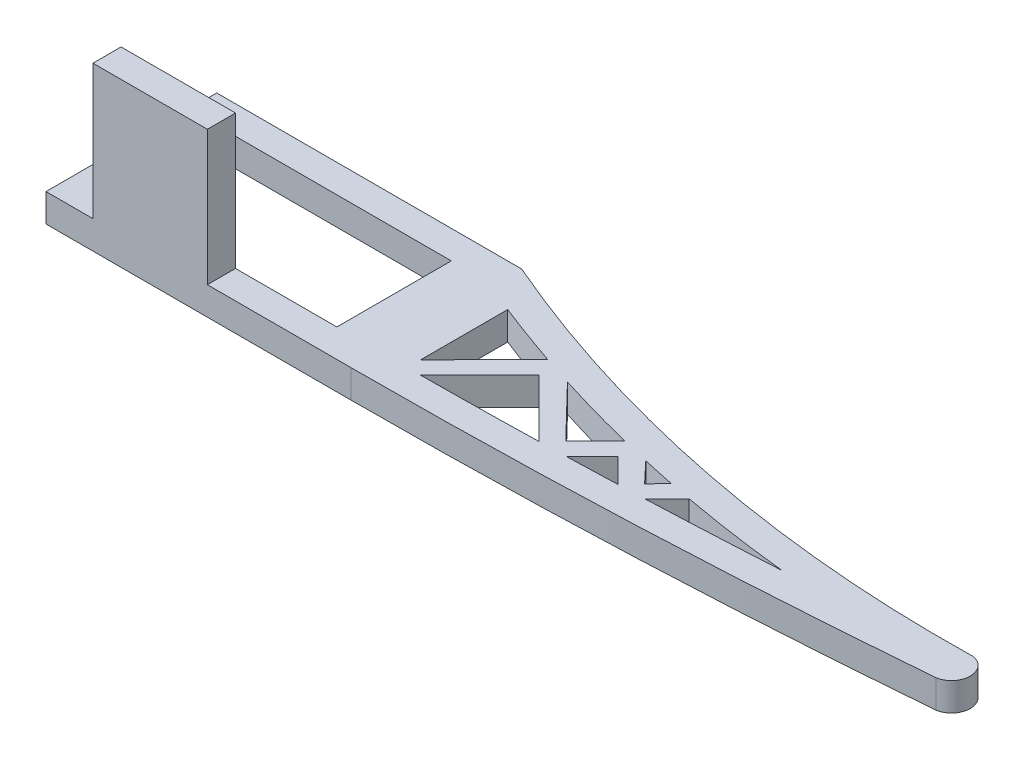
SolidWorks part; units mm, degrees
ref_plane "Front Plane" through (0, 0, 0) normal (0, 0, 1) x (1, 0, 0)
ref_plane "Top Plane" through (0, 0, 0) normal (0, 1, 0) x (1, 0, 0)
ref_plane "Right Plane" through (0, 0, 0) normal (1, 0, 0) x (0, 0, -1)
sketch "Sketch3" plane through (0, 0, 0) normal (0, 1, 0) x (1, 0, 0)
  line L1 (-11.25, 6.2) -> (11.75, 6.2)
  line L2 (-11.25, 6.2) -> (-11.25, -6)
  line L3 (-11.25, -6) -> (11.75, -6)
  line L4 (11.75, 6.2) -> (11.75, -6)
  line L5 (-16.25, 9.2) -> (16.25, 9.2)
  line L6 (-16.25, 9.2) -> (-16.25, -9)
  line L7 (-16.25, -9) -> (16.25, -9)
  line L13 (16.25, -9) -> (77.7339, -9) construction
  line L14 (77.7339, -9) -> (77.7339, 0.0031) construction
  line L15 (77.7339, -4.4984) -> (83.9654, -4.4984) construction
  line L16 (0, 0) -> (77.7339, 0.0031) construction
  arc A4 (76.0731, -6.4437) -> (76.0731, -2.5015) centre (75.7341, -4.4726) ccw
  arc A6 (16.25, -9) -> (76.0731, -6.4437) centre (16.25, 692.2678) ccw
  arc A10 (16.25, 9.2) -> (76.0731, -2.5015) centre (73.0415, 140.7708) ccw
  dimension "D6" = 2
  dimension "D1" = 12.2
  dimension "D2" = 23
  dimension "D3" = 32.5
  dimension "D4" = 18.2
  dimension "D5" = 3
extrude "Boss-Extrude1" add sketch "Sketch3" along normal blind 3
sketch "Sketch5" plane through (0, 3, 0) normal (0, 1, 0) x (1, 0, 0)
  line L1 (11.75, -6) -> (11.75, 6.2) construction
  line L2 (16.25, 9.2) -> (16.25, -9) construction
  line L3 (11.25, -9) -> (16.25, -9) construction
  line L4 (-16.25, -9) -> (16.25, -9) construction
  line L5 (11.75, 0.1) -> (11.75, -4.5) construction
  line L6 (19.25, -4.5) -> (19.3282, -4.5) construction
  line L8 (19.25, 4.714) -> (19.25, -4.5793)
  line L14 (20.6718, -5.986) -> (26.9906, 0.3328)
  line L15 (26.9906, 0.3328) -> (33.1196, -5.7962)
  line L16 (35.9529, -5.722) -> (38.6988, -2.9761)
  line L17 (38.6988, -2.9761) -> (41.2741, -5.5515)
  line L18 (44.1095, -5.444) -> (46.395, -3.0866)
  line L19 (19.25, -4.5793) -> (25.9777, 2.2429)
  line L20 (29.1124, 1.2172) -> (34.4991, -4.3473)
  line L21 (34.4991, -4.3473) -> (37.5887, -1.1731)
  line L22 (40.5625, -1.883) -> (42.6381, -4.087)
  line L23 (42.6381, -4.087) -> (44.0225, -2.6268)
  line L35 (19.25, 4.714) -> (19.25, -5.9936) construction
  arc A0 (16.25, 9.2) -> (76.0731, -2.5015) centre (73.0415, 140.7708) ccw construction
  arc A2 (35.9529, -5.722) -> (41.2741, -5.5515) centre (16.25, 692.2678) ccw
  arc A3 (44.1095, -5.444) -> (57.9535, -4.7535) centre (16.25, 692.2678) ccw
  arc A4 (20.6718, -5.986) -> (33.1196, -5.7962) centre (16.25, 692.2678) ccw
  arc A5 (19.25, 4.714) -> (25.9777, 2.2429) centre (73.0415, 140.7708) ccw
  arc A6 (19.25, 4.714) -> (76.1365, -5.5009) centre (73.0415, 140.7708) ccw construction
  arc A7 (40.5625, -1.883) -> (44.0225, -2.6268) centre (73.0415, 140.7708) ccw
  arc A8 (19.25, -5.9936) -> (75.8171, -3.4546) centre (16.25, 692.2678) ccw construction
  arc A9 (46.395, -3.0866) -> (57.9535, -4.7535) centre (73.0415, 140.7708) ccw
  arc A10 (29.1124, 1.2172) -> (37.5887, -1.1731) centre (73.0415, 140.7708) ccw
  arc A11 (16.25, -9) -> (76.0731, -6.4437) centre (16.25, 692.2678) ccw construction
extrude "Cut-Extrude1" cut sketch "Sketch5" against normal through all
sketch "Sketch7" plane through (0, 3, 0) normal (0, 1, 0) x (1, 0, 0)
  line L0 (-16.25, -9) -> (16.25, -9) construction
  line L1 (-11.25, -6) -> (0.95, -6)
  line L2 (-11.25, -6) -> (-11.25, -9)
  line L3 (-11.25, -9) -> (0.95, -9)
  line L4 (0.95, -6) -> (0.95, -9)
  dimension "D1" = 12.2
extrude "Boss-Extrude2" add sketch "Sketch7" along normal blind 14.35
